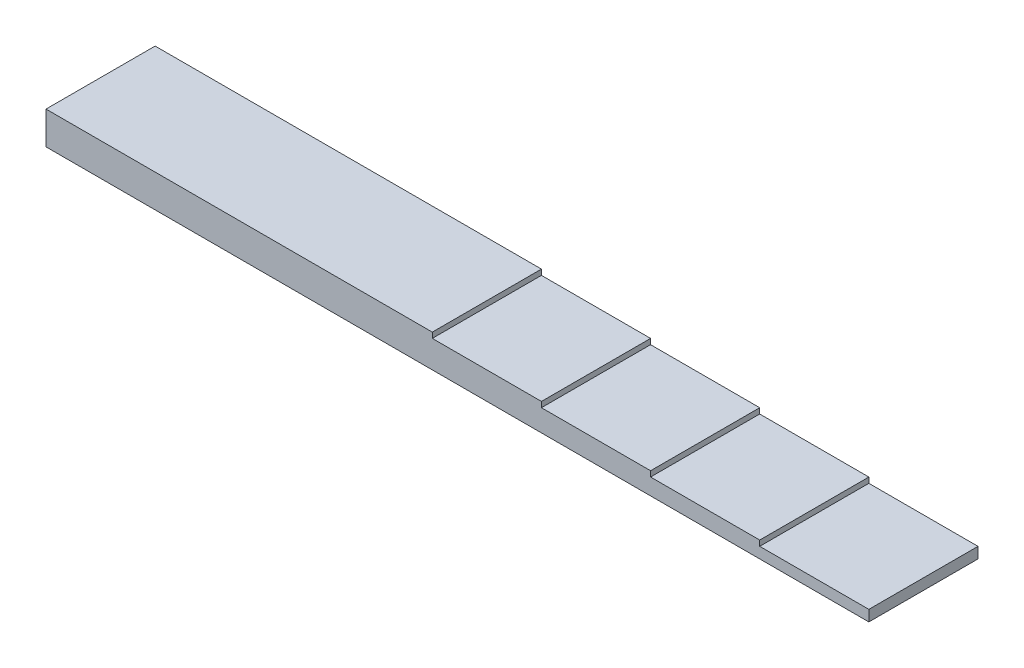
SolidWorks part; units mm, degrees
ref_plane "Plan de face" through (0, 0, 0) normal (0, 0, 1) x (1, 0, 0)
ref_plane "Plan de dessus" through (0, 0, 0) normal (0, 1, 0) x (1, 0, 0)
ref_plane "Plan de droite" through (0, 0, 0) normal (1, 0, 0) x (0, 0, -1)
sketch "Esquisse1" plane through (0, 0, 0) normal (0, 0, 1) x (1, 0, 0)
  line L1 (2.2885, -15.3025) -> (12.2885, -15.3025)
  line L3 (2.2885, -17.8025) -> (12.2885, -17.8025)
  line L4 (12.2885, -15.3025) -> (12.2885, -15.8025)
  line L5 (12.2885, -17.8025) -> (22.2885, -17.8025)
  line L7 (12.2885, -15.8025) -> (22.2885, -15.8025)
  line L8 (22.2885, -16.3025) -> (22.2885, -15.8025)
  line L9 (22.2885, -17.8025) -> (32.2885, -17.8025)
  line L11 (22.2885, -16.3025) -> (32.2885, -16.3025)
  line L12 (32.2885, -16.8025) -> (32.2885, -16.3025)
  line L13 (32.2885, -17.8025) -> (42.2885, -17.8025)
  line L15 (32.2885, -16.8025) -> (42.2885, -16.8025)
  line L16 (42.2885, -17.8025) -> (42.2885, -16.8025)
  line L17 (2.2885, -17.8025) -> (-33.1056, -17.8025)
  line L18 (2.2885, -15.3025) -> (2.2885, -14.8025)
  line L19 (2.2885, -14.8025) -> (-33.1056, -14.8025)
  line L20 (-33.1056, -17.8025) -> (-33.1056, -14.8025)
  dimension "D1" = 1
  dimension "D2" = 1.5
  dimension "D3" = 2
  dimension "D4" = 2.5
  dimension "D5" = 3
  dimension "D6" = 10
  dimension "D7" = 10
  dimension "D8" = 10
  dimension "D9" = 10
  dimension "D10" = 35.394
extrude "Boss.-Extru.1" add sketch "Esquisse1" along normal blind 10
